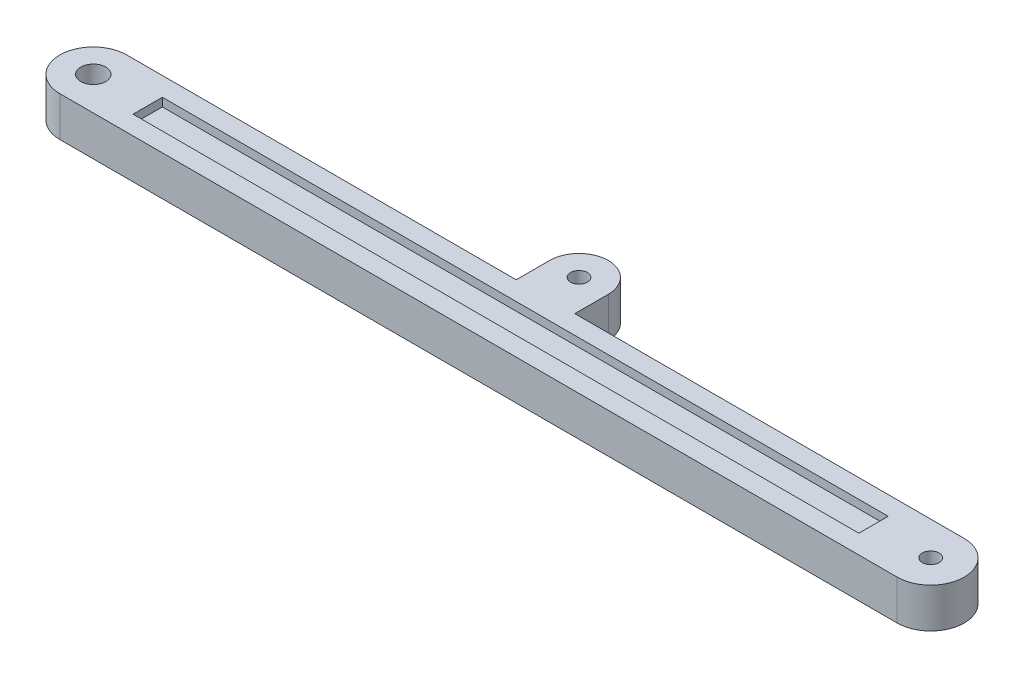
SolidWorks part; units mm, degrees
ref_plane "Front Plane" through (0, 0, 0) normal (0, 0, 1) x (1, 0, 0)
ref_plane "Top Plane" through (0, 0, 0) normal (0, 1, 0) x (1, 0, 0)
ref_plane "Right Plane" through (0, 0, 0) normal (1, 0, 0) x (0, 0, -1)
sketch "Sketch1" plane through (0, 0, 0) normal (0, 1, 0) x (1, 0, 0)
  line L0 (83, 24) -> (83, 16)
  line L1 (0, 0) -> (180, 0)
  line L2 (0, 0) -> (0, 16)
  line L3 (0, 16) -> (180, 16)
  line L4 (180, 0) -> (180, 16)
  line L5 (97, 24) -> (97, 16)
  line L6 (0, 8) -> (-10, 8) construction
  line L7 (-10, 16) -> (0, 16)
  line L8 (-10, 0) -> (0, 0)
  line L9 (180, 8) -> (190, 8) construction
  line L10 (180, 16) -> (190, 16)
  line L11 (180, 0) -> (190, 0)
  line L12 (-10, 8) -> (190, 8) construction
  circle A1 centre (90, 24) radius 2
  circle A3 centre (90, 24) radius 7
  circle A4 centre (-10, 8) radius 3
  circle A5 centre (-10, 8) radius 8
  circle A6 centre (190, 8) radius 2
  circle A7 centre (190, 8) radius 8
  dimension "D2" = 6
  dimension "D3" = 4
  dimension "D4" = 10
  dimension "D5" = 5
  dimension "D8" = 4
  dimension "D11" = 200
  dimension "D1" = 16
  dimension "D6" = 90
  dimension "D7" = 180
  dimension "D9" = 10
  dimension "D10" = 8
extrude "Boss-Extrude1" add sketch "Sketch1" along normal blind 9.5
sketch "Sketch2" plane through (0, 9.5, 0) normal (0, 1, 0) x (1, 0, 0)
  line L1 (3, 11.5) -> (176.3416, 11.5)
  line L2 (3, 11.5) -> (3, 4.5)
  line L3 (3, 4.5) -> (176.3416, 4.5)
  line L4 (176.3416, 11.5) -> (176.3416, 4.5)
  dimension "D1" = 7
  dimension "D2" = 3
extrude "Cut-Extrude1" cut sketch "Sketch2" against normal blind 2
